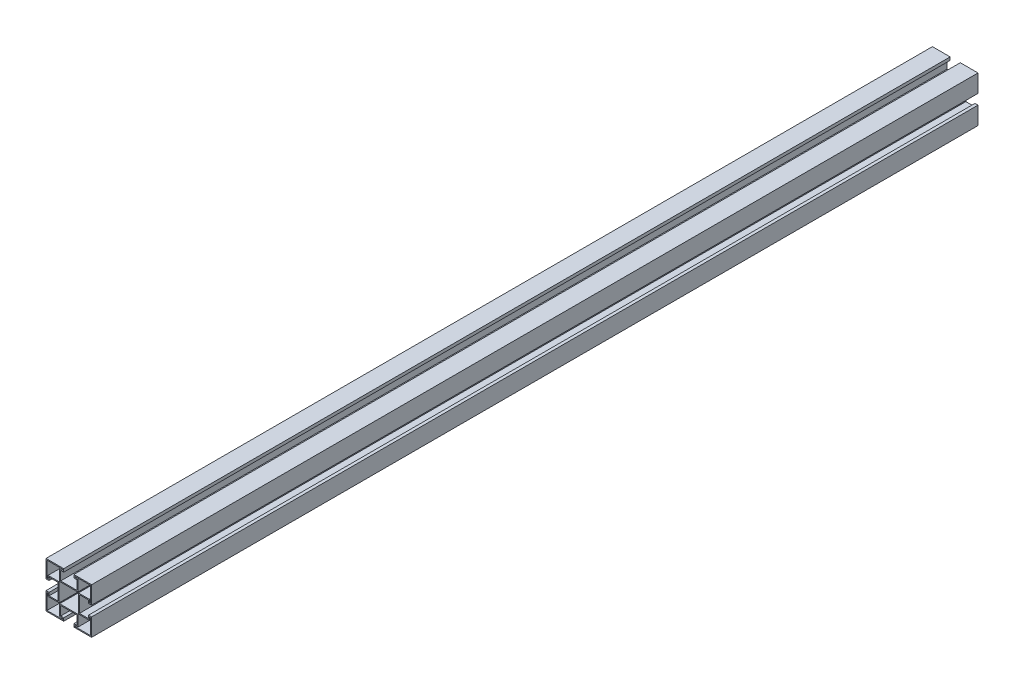
SolidWorks part; units mm, degrees
ref_plane "Ön Düzlem" through (0, 0, 0) normal (0, 0, 1) x (1, 0, 0)
ref_plane "Üst Düzlem" through (0, 0, 0) normal (0, 1, 0) x (1, 0, 0)
ref_plane "Sağ Düzlem" through (0, 0, 0) normal (1, 0, 0) x (0, 0, -1)
sketch "Sketch1" plane through (0, 0, 0) normal (0, 0, 1) x (1, 0, 0)
  line L0 (-5, 22.5) -> (-5, 19.5)
  line L1 (22.5, 22.5) -> (5, 22.5)
  line L2 (22.5, 22.5) -> (22.5, 5)
  line L3 (22.5, -22.5) -> (5, -22.5)
  line L4 (-22.5, 22.5) -> (-22.5, 5)
  line L5 (22.5, 22.5) -> (-22.5, -22.5) construction
  line L6 (22.5, -22.5) -> (-22.5, 22.5) construction
  line L7 (-5, 19.5) -> (-8, 19.5)
  line L8 (-8, 19.5) -> (-8, 10.5)
  line L9 (-8, 10.5) -> (8, 10.5)
  line L10 (8, 10.5) -> (8, 19.5)
  line L11 (8, 19.5) -> (5, 19.5)
  line L12 (5, 19.5) -> (5, 22.5)
  line L13 (22.5, 5) -> (19.5, 5)
  line L14 (19.5, 5) -> (19.5, 8)
  line L15 (19.5, 8) -> (10.5, 8)
  line L16 (10.5, 8) -> (10.5, -8)
  line L17 (10.5, -8) -> (19.5, -8)
  line L18 (19.5, -8) -> (19.5, -5)
  line L19 (19.5, -5) -> (22.5, -5)
  line L20 (0, 0) -> (22.5, 0) construction
  line L21 (0, 22.5) -> (0, 0) construction
  line L22 (-19.5, 5) -> (-19.5, 8)
  line L23 (-10.5, 8) -> (-10.5, -8)
  line L24 (-19.5, -8) -> (-19.5, -5)
  line L25 (-10.5, -8) -> (-19.5, -8)
  line L26 (-19.5, -5) -> (-22.5, -5)
  line L27 (-22.5, 5) -> (-19.5, 5)
  line L28 (-19.5, 8) -> (-10.5, 8)
  line L29 (-5, -22.5) -> (-5, -19.5)
  line L30 (5, -19.5) -> (5, -22.5)
  line L31 (8, -19.5) -> (5, -19.5)
  line L32 (8, -10.5) -> (8, -19.5)
  line L33 (-8, -10.5) -> (8, -10.5)
  line L34 (-8, -19.5) -> (-8, -10.5)
  line L35 (-5, -19.5) -> (-8, -19.5)
  line L36 (-5, -22.5) -> (-22.5, -22.5)
  line L37 (22.5, -5) -> (22.5, -22.5)
  line L38 (-5, 22.5) -> (-22.5, 22.5)
  line L39 (-22.5, -5) -> (-22.5, -22.5)
  line L40 (-5, 22.5) -> (5, 22.5) construction
  line L41 (22.5, 5) -> (22.5, -5) construction
  line L42 (-6, 21.5) -> (-21.5, 21.5)
  line L43 (-21.5, 21.5) -> (-21.5, 6)
  line L44 (-21.5, 6) -> (-20.5, 6)
  line L45 (-20.5, 6) -> (-20.5, 9)
  line L46 (-20.5, 9) -> (-9.5, 9)
  line L47 (-9.5, 9) -> (-9.5, -9)
  line L48 (-9.5, -9) -> (-20.5, -9)
  line L49 (-20.5, -9) -> (-20.5, -6)
  line L50 (-20.5, -6) -> (-21.5, -6)
  line L51 (-21.5, -6) -> (-21.5, -21.5)
  line L52 (-6, -21.5) -> (-21.5, -21.5)
  line L53 (-6, -21.5) -> (-6, -20.5)
  line L54 (-6, -20.5) -> (-9, -20.5)
  line L55 (-9, -20.5) -> (-9, -9.5)
  line L56 (-9, -9.5) -> (9, -9.5)
  line L57 (9, -9.5) -> (9, -20.5)
  line L58 (9, -20.5) -> (6, -20.5)
  line L59 (6, -20.5) -> (6, -21.5)
  line L60 (21.5, -21.5) -> (6, -21.5)
  line L61 (21.5, -6) -> (21.5, -21.5)
  line L62 (20.5, -6) -> (21.5, -6)
  line L63 (20.5, -9) -> (20.5, -6)
  line L64 (9.5, -9) -> (20.5, -9)
  line L65 (9.5, 9) -> (9.5, -9)
  line L66 (20.5, 9) -> (9.5, 9)
  line L67 (20.5, 6) -> (20.5, 9)
  line L68 (21.5, 6) -> (20.5, 6)
  line L69 (21.5, 21.5) -> (21.5, 6)
  line L70 (21.5, 21.5) -> (6, 21.5)
  line L71 (6, 20.5) -> (6, 21.5)
  line L72 (9, 20.5) -> (6, 20.5)
  line L73 (9, 9.5) -> (9, 20.5)
  line L74 (-9, 9.5) -> (9, 9.5)
  line L75 (-9, 20.5) -> (-9, 9.5)
  line L76 (-6, 20.5) -> (-9, 20.5)
  line L77 (-6, 21.5) -> (-6, 20.5)
  point P0 (0, 0)
  dimension "D1" = 45
  dimension "D2" = 3
  dimension "D3" = 10
  dimension "D4" = 10
  dimension "D5" = 12
  dimension "D6" = 12
  dimension "D7" = 1
extrude "Boss-Extrude2" add sketch "Sketch1" along normal mid plane 875 contours L26 L39 L36 L29 L35 L34 L33 L32 L31 L30 L3 L37 L19 L18 L17 L16 L15 L14 L13 L2 L1 L12 L11 L10 L9 L8 L7 L0 L38 L4 L27 L22 L28 L23 L25 L24 L42 L77 L76 L75 L74 L73 L72 L71 L70 L69 L68 L67 L66 L65
sketch "Sketch2" plane through (0, 22.5, 0) normal (0, 1, 0) x (1, 0, 0)
  line L0 (0, 437.5) -> (0, -437.5) construction
  line L1 (-8, 437.5) -> (8, 437.5) construction
  line L2 (-8, -437.5) -> (8, -437.5) construction
ref_plane "Plane1" through (0, 0, 0) normal (-1, 0, 0) x (0, 0, 1)
sketch "Sketch3" plane through (-22.5, 0, 0) normal (-1, 0, 0) x (0, 0, 1)
  line L0 (437.5, 0) -> (-437.5, 0) construction
  line L1 (437.5, 8) -> (437.5, -8) construction
  line L2 (-437.5, 8) -> (-437.5, -8) construction
sketch "Sketch4" plane through (22.5, 0, 0) normal (1, 0, 0) x (0, 0, -1)
  line L0 (437.5, 0) -> (-437.5, 0) construction
ref_plane "Plane2" through (0, 0, 0) normal (0, 1, 0) x (1, 0, 0)
ref_plane "Plane3" through (0, 0, 0) normal (0, 1, 0) x (1, 0, 0)
